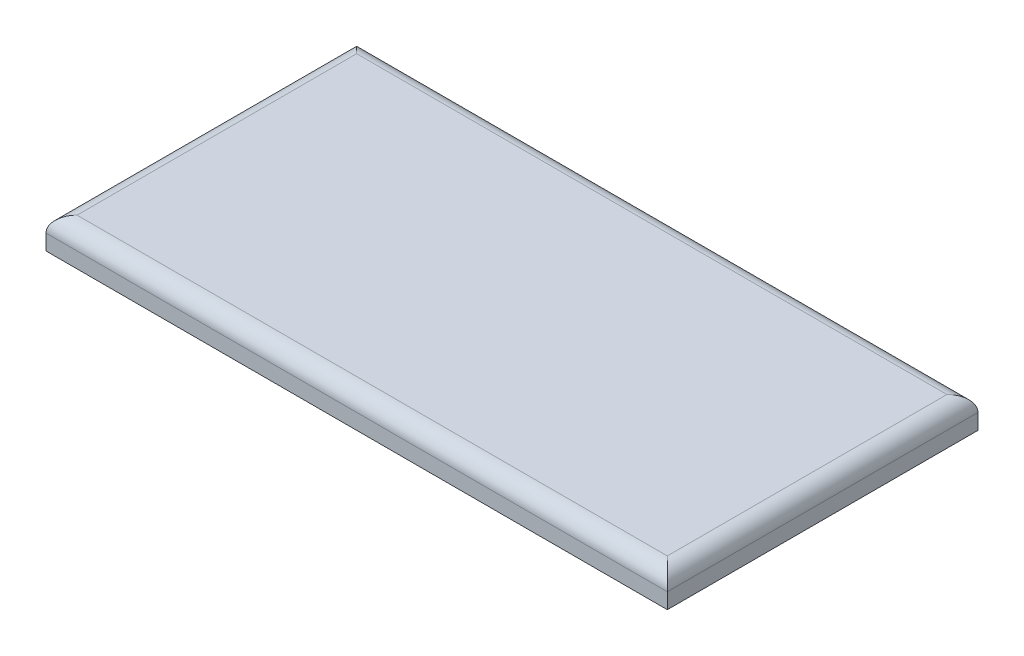
SolidWorks part; units mm, degrees
ref_plane "Front Plane" through (0, 0, 0) normal (0, 0, 1) x (1, 0, 0)
ref_plane "Top Plane" through (0, 0, 0) normal (0, 1, 0) x (1, 0, 0)
ref_plane "Right Plane" through (0, 0, 0) normal (1, 0, 0) x (0, 0, -1)
sketch "Sketch1" plane through (0, 0, 0) normal (0, 1, 0) x (1, 0, 0)
  line L1 (-64.6449, 17.1438) -> (87.7551, 17.1438)
  line L2 (-64.6449, 17.1438) -> (-64.6449, -59.0562)
  line L3 (-64.6449, -59.0562) -> (87.7551, -59.0562)
  line L4 (87.7551, 17.1438) -> (87.7551, -59.0562)
  dimension "D1" = 152.4
  dimension "D2" = 76.2
extrude "Boss-Extrude1" add sketch "Sketch1" along normal blind 7.62
fillet "Fillet1" radius 3.81 4 edges at (87.7551, 7.62, 20.9562) (11.5551, 7.62, -17.1438) (11.5551, 7.62, 59.0562) (-64.6449, 7.62, 20.9562)
sketch "Sketch5" plane through (0, 7.62, 0) normal (0, 1, 0) x (1, 0, 0)
  line L0 (-35.4349, -22.0105) -> (-23.4667, -44.4142)
  line L5 (-23.4667, -44.4142) -> (-4.2528, -44.4142)
  line L9 (-4.2528, -44.4142) -> (2.6651, -27.9816)
  line L12 (-16.2209, -22.0105) -> (-35.4349, -22.0105)
  line L13 (-35.4349, -22.0105) -> (-25.675, -5.6506)
  line L14 (-25.675, -5.6506) -> (-9.1067, -5.9454)
  line L15 (-16.2209, -22.0105) -> (-4.2528, -44.4142)
  line L28 (-25.675, -5.6506) -> (-28.6678, -0.0482)
  line L29 (-28.6678, -0.0482) -> (-3.0665, 0.3703)
  line L39 (15.0126, -33.4727) -> (22.3847, -24.8064)
  line L40 (22.3847, -24.8064) -> (4.3056, 9.0366)
  line L41 (4.3056, 9.0366) -> (-3.0665, 0.3703)
  line L43 (4.3056, 9.0366) -> (-22.7349, 8.6181)
  line L44 (-22.7349, 8.6181) -> (-28.6678, -0.0482)
  line L45 (-3.0665, 0.3703) -> (15.0126, -33.4727)
  line L47 (-60.8349, 13.3338) -> (-60.8349, -55.2462) construction
  line L48 (15.0126, -33.4727) -> (0.2519, -33.714)
  line L49 (-48.1349, -52.831) -> (-48.1349, -44.4142)
  line L50 (-35.4349, -52.831) -> (-35.4349, -44.4142)
  line L51 (-22.7349, -52.831) -> (-22.7349, -44.4142)
  line L52 (-10.0349, -52.831) -> (-10.0349, -44.4142)
  line L53 (2.6651, -52.831) -> (2.6651, -44.4142)
  line L54 (28.0651, -52.831) -> (28.0651, -44.4142)
  line L55 (40.7651, -52.831) -> (40.7651, -44.4142)
  line L56 (53.4651, -52.831) -> (53.4651, -44.4142)
  line L57 (66.1651, -52.831) -> (66.1651, -44.4142)
  line L58 (78.8651, -52.831) -> (78.8651, -44.4142)
  line L59 (15.3651, -52.831) -> (15.3651, -44.4142)
  line L60 (-9.1067, -5.9454) -> (-16.2209, -22.0105)
  line L61 (-9.1067, -5.9454) -> (2.6651, -27.9816)
  text T0 "WESLEY GARNES"
  text T1 "<b>.50</b>"
  point P11 (0, 0)
  point P13 (0, 0)
  point P37 (-48.1349, -48.6226)
  dimension "D1" = 12.7
  dimension "D2" = 12.7
  dimension "D3" = 12.7
  dimension "D4" = 12.7
  dimension "D5" = 12.7
  dimension "D6" = 12.7
  dimension "D7" = 12.7
  dimension "D8" = 12.7
  dimension "D9" = 12.7
  dimension "D10" = 12.7
  dimension "D11" = 12.7
